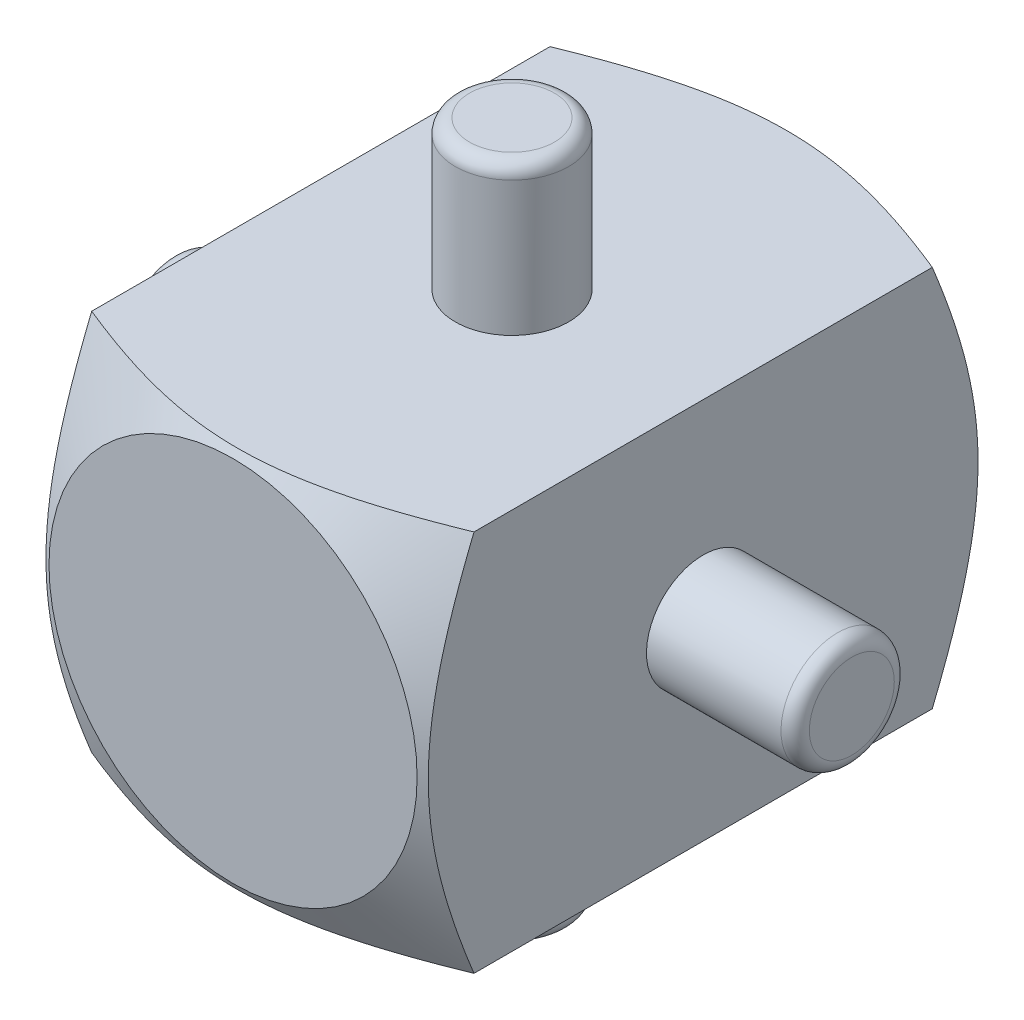
SolidWorks part; units mm, degrees
ref_plane "Front Plane" through (0, 0, 0) normal (0, 0, 1) x (1, 0, 0)
ref_plane "Top Plane" through (0, 0, 0) normal (0, 1, 0) x (1, 0, 0)
ref_plane "Right Plane" through (0, 0, 0) normal (1, 0, 0) x (0, 0, -1)
sketch "Sketch1" plane through (0, 0, 0) normal (0, 0, 1) x (1, 0, 0)
  line L1 (-6.75, 6.75) -> (6.75, 6.75)
  line L2 (-6.75, 6.75) -> (-6.75, -6.75)
  line L3 (-6.75, -6.75) -> (6.75, -6.75)
  line L4 (6.75, 6.75) -> (6.75, -6.75)
  dimension "D1" = 13.5
  dimension "D2" = 13.5
  dimension "D3" = 6.75
  dimension "D4" = 6.75
extrude "Boss-Extrude1" add sketch "Sketch1" along normal blind 19.7
sketch "Sketch2" plane through (0, 0, 0) normal (0, 1, 0) x (1, 0, 0)
  line L0 (0, -20.7153) -> (0, 6.1722) construction
  line L1 (-6.5, 0) -> (-15.39, 0)
  line L2 (-15.39, 0) -> (-15.39, -19.7)
  line L3 (-15.39, -19.7) -> (-6.5, -19.7)
  line L4 (-6.5, -19.7) -> (-12.85, -16.0338)
  line L5 (-12.85, -16.0338) -> (-12.85, -3.6662)
  line L6 (-12.85, -3.6662) -> (-6.5, 0)
  line L7 (6.75, 0) -> (-6.75, 0) construction
  line L9 (-6.75, -19.7) -> (-6.75, 0) construction
  line L10 (6.75, -19.7) -> (-6.75, -19.7) construction
  dimension "D1" = 6.35
  dimension "D2" = 2.54
  dimension "D3" = 30
  dimension "D4" = 30
  dimension "D5" = 0.25
  dimension "D6" = 0.25
revolve "Cut-Revolve1" cut sketch "Sketch2" angle 360 about L0
sketch "Sketch3" plane through (0, 0, 0) normal (0, 1, 0) x (1, 0, 0)
  circle A0 centre (0, -9.85) radius 2
  dimension "D1" = 4
  dimension "D2" = 9.85
extrude "Boss-Extrude2" add sketch "Sketch3" along normal mid plane 24
sketch "Sketch4" plane through (0, 0, 0) normal (1, 0, 0) x (0, 0, -1)
  line L0 (-17.9414, 6.75) -> (-1.7586, 6.75) construction
  line L2 (-19.7, 6.5) -> (-19.7, -6.5) construction
  circle A0 centre (-9.85, 0) radius 2
  point P2 (0, 0)
  point P5 (0, 0)
  point P8 (0, 0)
  dimension "D1" = 4
  dimension "D2" = 6.75
  dimension "D3" = 9.85
extrude "Boss-Extrude3" add sketch "Sketch4" along normal mid plane 24 contours A0
fillet "Fillet1" radius 0.5 4 edges at (0, -12, 11.85) (0, 12, 11.85) (-12, 0, 7.85) (12, 0, 7.85)
